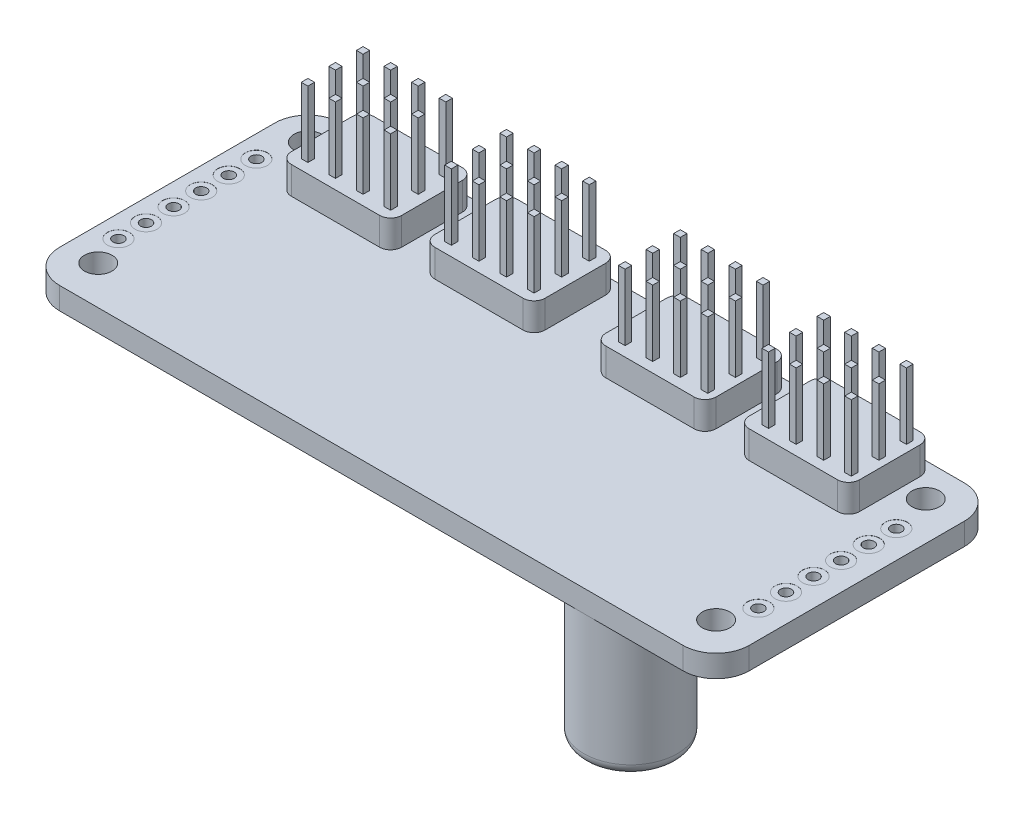
SolidWorks part; units mm, degrees
ref_plane "Front" through (0, 0, 0) normal (0, 0, 1) x (1, 0, 0)
ref_plane "Top" through (0, 0, 0) normal (0, 1, 0) x (1, 0, 0)
ref_plane "Right" through (0, 0, 0) normal (1, 0, 0) x (0, 0, -1)
sketch "Sketch1" plane through (0, 0, 0) normal (0, 1, 0) x (1, 0, 0)
  line L0 (-31.25, 12.75) -> (31.25, -12.75) construction
  line L1 (-31.25, 12.75) -> (31.25, 12.75)
  line L2 (-31.25, 12.75) -> (-31.25, -12.75)
  line L3 (-31.25, -12.75) -> (31.25, -12.75)
  line L4 (31.25, 12.75) -> (31.25, -12.75)
  dimension "D1" = 62.5
  dimension "D2" = 25.5
extrude "Boss-Extrude1" add sketch "Sketch1" along normal blind 2
fillet "Fillet1" radius 3 4 edges at (-31.25, 1, -12.75) (-31.25, 1, 12.75) (31.25, 1, -12.75) (31.25, 1, 12.75)
sketch "Sketch2" plane through (0, 2, 0) normal (0, 1, 0) x (1, 0, 0)
  line L0 (-31.25, 9.75) -> (-31.25, -9.75) construction
  line L1 (-25.75, 12.25) -> (-15.75, 12.25)
  line L2 (-25.75, 12.25) -> (-25.75, 4.75)
  line L3 (-25.75, 4.75) -> (-15.75, 4.75)
  line L4 (-15.75, 12.25) -> (-15.75, 4.75)
  line L5 (-12.75, 12.25) -> (-2.75, 12.25)
  line L6 (-12.75, 12.25) -> (-12.75, 4.75)
  line L7 (-12.75, 4.75) -> (-2.75, 4.75)
  line L8 (-2.75, 12.25) -> (-2.75, 4.75)
  line L9 (2.75, 12.25) -> (12.75, 12.25)
  line L10 (2.75, 12.25) -> (2.75, 4.75)
  line L11 (2.75, 4.75) -> (12.75, 4.75)
  line L12 (12.75, 12.25) -> (12.75, 4.75)
  line L13 (15.75, 12.25) -> (25.75, 12.25)
  line L14 (15.75, 12.25) -> (15.75, 4.75)
  line L15 (15.75, 4.75) -> (25.75, 4.75)
  line L16 (25.75, 12.25) -> (25.75, 4.75)
  line L17 (28.25, 12.75) -> (-28.25, 12.75) construction
  dimension "D1" = 5.5
  dimension "D2" = 3
  dimension "D3" = 5.5
  dimension "D4" = 3
  dimension "D5" = 10
  dimension "D6" = 7.5
  dimension "D7" = 0.5
extrude "Boss-Extrude2" add sketch "Sketch2" along normal blind 2.5
fillet "Fillet2" radius 1 16 edges at (-25.75, 3.25, -12.25) (-15.75, 3.25, -12.25) (-12.75, 3.25, -12.25) (-2.75, 3.25, -12.25) (2.75, 3.25, -12.25) (12.75, 3.25, -12.25) (15.75, 3.25, -12.25) (25.75, 3.25, -12.25) (25.75, 3.25, -4.75) (15.75, 3.25, -4.75) (2.75, 3.25, -4.75) (-2.75, 3.25, -4.75) (-12.75, 3.25, -4.75) (-25.75, 3.25, -4.75) (-15.75, 3.25, -4.75) (12.75, 3.25, -4.75)
sketch "Sketch3" plane through (0, 4.5, 0) normal (0, 1, 0) x (1, 0, 0)
  line L0 (-24.15, 10.95) -> (-25.75, 10.95) construction
  line L1 (-24.75, 11.25) -> (-24.15, 11.25)
  line L2 (-24.75, 11.25) -> (-24.75, 10.65)
  line L3 (-24.75, 10.65) -> (-24.15, 10.65)
  line L4 (-24.15, 11.25) -> (-24.15, 10.65)
  line L5 (-25.75, 11.25) -> (-25.75, 5.75) construction
  line L6 (-24.45, 10.65) -> (-24.45, 12.25) construction
  line L7 (-16.75, 12.25) -> (-24.75, 12.25) construction
  line L8 (-22.25, 10.65) -> (-21.65, 10.65)
  line L9 (-22.25, 11.25) -> (-22.25, 10.65)
  line L10 (-22.25, 11.25) -> (-21.65, 11.25)
  line L11 (-21.65, 11.25) -> (-21.65, 10.65)
  line L12 (-19.75, 10.65) -> (-19.15, 10.65)
  line L13 (-19.75, 11.25) -> (-19.75, 10.65)
  line L14 (-19.75, 11.25) -> (-19.15, 11.25)
  line L15 (-19.15, 11.25) -> (-19.15, 10.65)
  line L16 (-17.25, 10.65) -> (-16.65, 10.65)
  line L17 (-17.25, 11.25) -> (-17.25, 10.65)
  line L18 (-17.25, 11.25) -> (-16.65, 11.25)
  line L19 (-16.65, 11.25) -> (-16.65, 10.65)
  line L20 (-22.25, 8.15) -> (-21.65, 8.15)
  line L21 (-22.25, 8.75) -> (-22.25, 8.15)
  line L22 (-22.25, 8.75) -> (-21.65, 8.75)
  line L23 (-21.65, 8.75) -> (-21.65, 8.15)
  line L24 (-19.75, 8.15) -> (-19.15, 8.15)
  line L25 (-19.75, 8.75) -> (-19.75, 8.15)
  line L26 (-19.75, 8.75) -> (-19.15, 8.75)
  line L27 (-19.15, 8.75) -> (-19.15, 8.15)
  line L28 (-17.25, 8.15) -> (-16.65, 8.15)
  line L29 (-17.25, 8.75) -> (-17.25, 8.15)
  line L30 (-17.25, 8.75) -> (-16.65, 8.75)
  line L31 (-16.65, 8.75) -> (-16.65, 8.15)
  line L32 (-22.25, 5.65) -> (-21.65, 5.65)
  line L33 (-22.25, 6.25) -> (-22.25, 5.65)
  line L34 (-22.25, 6.25) -> (-21.65, 6.25)
  line L35 (-21.65, 6.25) -> (-21.65, 5.65)
  line L36 (-19.75, 5.65) -> (-19.15, 5.65)
  line L37 (-19.75, 6.25) -> (-19.75, 5.65)
  line L38 (-19.75, 6.25) -> (-19.15, 6.25)
  line L39 (-19.15, 6.25) -> (-19.15, 5.65)
  line L40 (-17.25, 5.65) -> (-16.65, 5.65)
  line L41 (-17.25, 6.25) -> (-17.25, 5.65)
  line L42 (-17.25, 6.25) -> (-16.65, 6.25)
  line L43 (-16.65, 6.25) -> (-16.65, 5.65)
  line L44 (-24.75, 8.15) -> (-24.15, 8.15)
  line L45 (-24.75, 8.75) -> (-24.75, 8.15)
  line L46 (-24.75, 8.75) -> (-24.15, 8.75)
  line L47 (-24.15, 8.75) -> (-24.15, 8.15)
  line L48 (-24.75, 5.65) -> (-24.15, 5.65)
  line L49 (-24.75, 6.25) -> (-24.75, 5.65)
  line L50 (-24.75, 6.25) -> (-24.15, 6.25)
  line L51 (-24.15, 6.25) -> (-24.15, 5.65)
  line L52 (-11.75, 11.25) -> (-11.15, 11.25)
  line L53 (-11.75, 11.25) -> (-11.75, 10.65)
  line L54 (-11.75, 10.65) -> (-11.15, 10.65)
  line L55 (-11.15, 11.25) -> (-11.15, 10.65)
  line L56 (-9.25, 10.65) -> (-8.65, 10.65)
  line L57 (-9.25, 11.25) -> (-9.25, 10.65)
  line L58 (-9.25, 11.25) -> (-8.65, 11.25)
  line L59 (-8.65, 11.25) -> (-8.65, 10.65)
  line L60 (-6.75, 10.65) -> (-6.15, 10.65)
  line L61 (-6.75, 11.25) -> (-6.75, 10.65)
  line L62 (-6.75, 11.25) -> (-6.15, 11.25)
  line L63 (-6.15, 11.25) -> (-6.15, 10.65)
  line L64 (-4.25, 10.65) -> (-3.65, 10.65)
  line L65 (-4.25, 11.25) -> (-4.25, 10.65)
  line L66 (-4.25, 11.25) -> (-3.65, 11.25)
  line L67 (-3.65, 11.25) -> (-3.65, 10.65)
  line L68 (-9.25, 8.15) -> (-8.65, 8.15)
  line L69 (-9.25, 8.75) -> (-9.25, 8.15)
  line L70 (-9.25, 8.75) -> (-8.65, 8.75)
  line L71 (-8.65, 8.75) -> (-8.65, 8.15)
  line L72 (-6.75, 8.15) -> (-6.15, 8.15)
  line L73 (-6.75, 8.75) -> (-6.75, 8.15)
  line L74 (-6.75, 8.75) -> (-6.15, 8.75)
  line L75 (-6.15, 8.75) -> (-6.15, 8.15)
  line L76 (-4.25, 8.15) -> (-3.65, 8.15)
  line L77 (-4.25, 8.75) -> (-4.25, 8.15)
  line L78 (-4.25, 8.75) -> (-3.65, 8.75)
  line L79 (-3.65, 8.75) -> (-3.65, 8.15)
  line L80 (-9.25, 5.65) -> (-8.65, 5.65)
  line L81 (-9.25, 6.25) -> (-9.25, 5.65)
  line L82 (-9.25, 6.25) -> (-8.65, 6.25)
  line L83 (-8.65, 6.25) -> (-8.65, 5.65)
  line L84 (-6.75, 5.65) -> (-6.15, 5.65)
  line L85 (-6.75, 6.25) -> (-6.75, 5.65)
  line L86 (-6.75, 6.25) -> (-6.15, 6.25)
  line L87 (-6.15, 6.25) -> (-6.15, 5.65)
  line L88 (-4.25, 5.65) -> (-3.65, 5.65)
  line L89 (-4.25, 6.25) -> (-4.25, 5.65)
  line L90 (-4.25, 6.25) -> (-3.65, 6.25)
  line L91 (-3.65, 6.25) -> (-3.65, 5.65)
  line L92 (-11.75, 8.15) -> (-11.15, 8.15)
  line L93 (-11.75, 8.75) -> (-11.75, 8.15)
  line L94 (-11.75, 8.75) -> (-11.15, 8.75)
  line L95 (-11.15, 8.75) -> (-11.15, 8.15)
  line L96 (-11.75, 5.65) -> (-11.15, 5.65)
  line L97 (-11.75, 6.25) -> (-11.75, 5.65)
  line L98 (-11.75, 6.25) -> (-11.15, 6.25)
  line L99 (-11.15, 6.25) -> (-11.15, 5.65)
  line L100 (-11.15, 10.95) -> (-12.75, 10.95) construction
  line L101 (-11.45, 10.65) -> (-11.45, 12.25) construction
  line L102 (4, 11.25) -> (4.6, 11.25)
  line L103 (4, 11.25) -> (4, 10.65)
  line L104 (4, 10.65) -> (4.6, 10.65)
  line L105 (4.6, 11.25) -> (4.6, 10.65)
  line L106 (6.5, 10.65) -> (7.1, 10.65)
  line L107 (6.5, 11.25) -> (6.5, 10.65)
  line L108 (6.5, 11.25) -> (7.1, 11.25)
  line L109 (7.1, 11.25) -> (7.1, 10.65)
  line L110 (9, 10.65) -> (9.6, 10.65)
  line L111 (9, 11.25) -> (9, 10.65)
  line L112 (9, 11.25) -> (9.6, 11.25)
  line L113 (9.6, 11.25) -> (9.6, 10.65)
  line L114 (11.5, 10.65) -> (12.1, 10.65)
  line L115 (11.5, 11.25) -> (11.5, 10.65)
  line L116 (11.5, 11.25) -> (12.1, 11.25)
  line L117 (12.1, 11.25) -> (12.1, 10.65)
  line L118 (6.5, 8.15) -> (7.1, 8.15)
  line L119 (6.5, 8.75) -> (6.5, 8.15)
  line L120 (6.5, 8.75) -> (7.1, 8.75)
  line L121 (7.1, 8.75) -> (7.1, 8.15)
  line L122 (9, 8.15) -> (9.6, 8.15)
  line L123 (9, 8.75) -> (9, 8.15)
  line L124 (9, 8.75) -> (9.6, 8.75)
  line L125 (9.6, 8.75) -> (9.6, 8.15)
  line L126 (11.5, 8.15) -> (12.1, 8.15)
  line L127 (11.5, 8.75) -> (11.5, 8.15)
  line L128 (11.5, 8.75) -> (12.1, 8.75)
  line L129 (12.1, 8.75) -> (12.1, 8.15)
  line L130 (6.5, 5.65) -> (7.1, 5.65)
  line L131 (6.5, 6.25) -> (6.5, 5.65)
  line L132 (6.5, 6.25) -> (7.1, 6.25)
  line L133 (7.1, 6.25) -> (7.1, 5.65)
  line L134 (9, 5.65) -> (9.6, 5.65)
  line L135 (9, 6.25) -> (9, 5.65)
  line L136 (9, 6.25) -> (9.6, 6.25)
  line L137 (9.6, 6.25) -> (9.6, 5.65)
  line L138 (11.5, 5.65) -> (12.1, 5.65)
  line L139 (11.5, 6.25) -> (11.5, 5.65)
  line L140 (11.5, 6.25) -> (12.1, 6.25)
  line L141 (12.1, 6.25) -> (12.1, 5.65)
  line L142 (4, 8.15) -> (4.6, 8.15)
  line L143 (4, 8.75) -> (4, 8.15)
  line L144 (4, 8.75) -> (4.6, 8.75)
  line L145 (4.6, 8.75) -> (4.6, 8.15)
  line L146 (4, 5.65) -> (4.6, 5.65)
  line L147 (4, 6.25) -> (4, 5.65)
  line L148 (4, 6.25) -> (4.6, 6.25)
  line L149 (4.6, 6.25) -> (4.6, 5.65)
  line L150 (4.6, 10.95) -> (3, 10.95) construction
  line L151 (4.3, 10.65) -> (4.3, 12.25) construction
  line L152 (17, 11.25) -> (17.6, 11.25)
  line L153 (17, 11.25) -> (17, 10.65)
  line L154 (17, 10.65) -> (17.6, 10.65)
  line L155 (17.6, 11.25) -> (17.6, 10.65)
  line L156 (19.5, 10.65) -> (20.1, 10.65)
  line L157 (19.5, 11.25) -> (19.5, 10.65)
  line L158 (19.5, 11.25) -> (20.1, 11.25)
  line L159 (20.1, 11.25) -> (20.1, 10.65)
  line L160 (22, 10.65) -> (22.6, 10.65)
  line L161 (22, 11.25) -> (22, 10.65)
  line L162 (22, 11.25) -> (22.6, 11.25)
  line L163 (22.6, 11.25) -> (22.6, 10.65)
  line L164 (24.5, 10.65) -> (25.1, 10.65)
  line L165 (24.5, 11.25) -> (24.5, 10.65)
  line L166 (24.5, 11.25) -> (25.1, 11.25)
  line L167 (25.1, 11.25) -> (25.1, 10.65)
  line L168 (19.5, 8.15) -> (20.1, 8.15)
  line L169 (19.5, 8.75) -> (19.5, 8.15)
  line L170 (19.5, 8.75) -> (20.1, 8.75)
  line L171 (20.1, 8.75) -> (20.1, 8.15)
  line L172 (22, 8.15) -> (22.6, 8.15)
  line L173 (22, 8.75) -> (22, 8.15)
  line L174 (22, 8.75) -> (22.6, 8.75)
  line L175 (22.6, 8.75) -> (22.6, 8.15)
  line L176 (24.5, 8.15) -> (25.1, 8.15)
  line L177 (24.5, 8.75) -> (24.5, 8.15)
  line L178 (24.5, 8.75) -> (25.1, 8.75)
  line L179 (25.1, 8.75) -> (25.1, 8.15)
  line L180 (19.5, 5.65) -> (20.1, 5.65)
  line L181 (19.5, 6.25) -> (19.5, 5.65)
  line L182 (19.5, 6.25) -> (20.1, 6.25)
  line L183 (20.1, 6.25) -> (20.1, 5.65)
  line L184 (22, 5.65) -> (22.6, 5.65)
  line L185 (22, 6.25) -> (22, 5.65)
  line L186 (22, 6.25) -> (22.6, 6.25)
  line L187 (22.6, 6.25) -> (22.6, 5.65)
  line L188 (24.5, 5.65) -> (25.1, 5.65)
  line L189 (24.5, 6.25) -> (24.5, 5.65)
  line L190 (24.5, 6.25) -> (25.1, 6.25)
  line L191 (25.1, 6.25) -> (25.1, 5.65)
  line L192 (17, 8.15) -> (17.6, 8.15)
  line L193 (17, 8.75) -> (17, 8.15)
  line L194 (17, 8.75) -> (17.6, 8.75)
  line L195 (17.6, 8.75) -> (17.6, 8.15)
  line L196 (17, 5.65) -> (17.6, 5.65)
  line L197 (17, 6.25) -> (17, 5.65)
  line L198 (17, 6.25) -> (17.6, 6.25)
  line L199 (17.6, 6.25) -> (17.6, 5.65)
  dimension "D1" = 0.6
  dimension "D2" = 1.6
  dimension "D3" = 1.6
  dimension "D4" = 4
  dimension "D5" = 3
  dimension "D6" = 2
  dimension "D7" = 2
extrude "Boss-Extrude3" add sketch "Sketch3" along normal blind 6
sketch "Sketch4" plane through (0, 2, 0) normal (0, 1, 0) x (1, 0, 0)
  line L0 (-31.25, 9.75) -> (-31.25, -9.75) construction
  line L1 (28.25, 12.75) -> (-28.25, 12.75) construction
  circle A0 centre (-28.25, 9.75) radius 1.25
  circle A1 centre (27.75, 9.75) radius 1.25
  circle A2 centre (27.75, -9.25) radius 1.25
  circle A3 centre (-28.25, -9.25) radius 1.25
  dimension "D1" = 2.5
  dimension "D4" = 56
  dimension "D5" = 19
  dimension "D6" = 3
  dimension "D7" = 3
  dimension "D2" = 2
  dimension "D3" = 2
extrude "Cut-Extrude1" cut sketch "Sketch4" against normal through all
sketch "Sketch5" plane through (0, 0, 0) normal (0, 1, 0) x (1, 0, 0)
  line L0 (31.25, -9.75) -> (31.25, 9.75) construction
  line L1 (-28.25, -12.75) -> (28.25, -12.75) construction
  circle A0 centre (19.25, -8.5) radius 4.25
  dimension "D1" = 8.5
  dimension "D2" = 12
extrude "Boss-Extrude4" add sketch "Sketch5" against normal blind 12
fillet "Fillet3" radius 1 1 edges at (19.25, -12, 12.75)
sketch "Sketch6" plane through (0, 2, 0) normal (0, 1, 0) x (1, 0, 0)
  line L0 (-31.25, 9.75) -> (-31.25, -9.75) construction
  circle A0 centre (-29.25, 6.0811) radius 0.5
  circle A1 centre (-29.25, 3.5811) radius 0.5
  circle A2 centre (-29.25, 1.0811) radius 0.5
  circle A3 centre (-29.25, -1.4189) radius 0.5
  circle A4 centre (-29.25, -3.9189) radius 0.5
  circle A5 centre (-29.25, -6.4189) radius 0.5
  circle A6 centre (28.75, 3.5811) radius 0.5
  circle A7 centre (28.75, 6.0811) radius 0.5
  circle A8 centre (28.75, 1.0811) radius 0.5
  circle A9 centre (28.75, -1.4189) radius 0.5
  circle A10 centre (28.75, -3.9189) radius 0.5
  circle A11 centre (28.75, -6.4189) radius 0.5
  dimension "D1" = 1
  dimension "D3" = 2
  dimension "D2" = 6
  dimension "D4" = 2
extrude "Cut-Extrude2" cut sketch "Sketch6" against normal through all
sketch "Sketch7" plane through (0, 2, 0) normal (0, 1, 0) x (1, 0, 0)
  circle A39 centre (-29.25, 3.5811) radius 1
  circle A40 centre (-29.25, 6.0811) radius 1
  circle A41 centre (-29.25, 6.0811) radius 1
  circle A42 centre (-29.25, 1.0811) radius 1
  circle A43 centre (-29.25, -1.4189) radius 1
  circle A44 centre (-29.25, -3.9189) radius 1
  circle A45 centre (-29.25, -6.4189) radius 1
  circle A46 centre (28.75, 6.0811) radius 1
  circle A47 centre (28.75, 3.5811) radius 1
  circle A48 centre (28.75, 1.0811) radius 1
  circle A49 centre (28.75, -1.4189) radius 1
  circle A50 centre (28.75, -3.9189) radius 1
  circle A51 centre (28.75, -6.4189) radius 1
  dimension "D1" = 0.5
  dimension "D2" = 6
  dimension "D3" = 2
extrude "Cut-Extrude3" cut sketch "Sketch7" against normal blind 0.01
